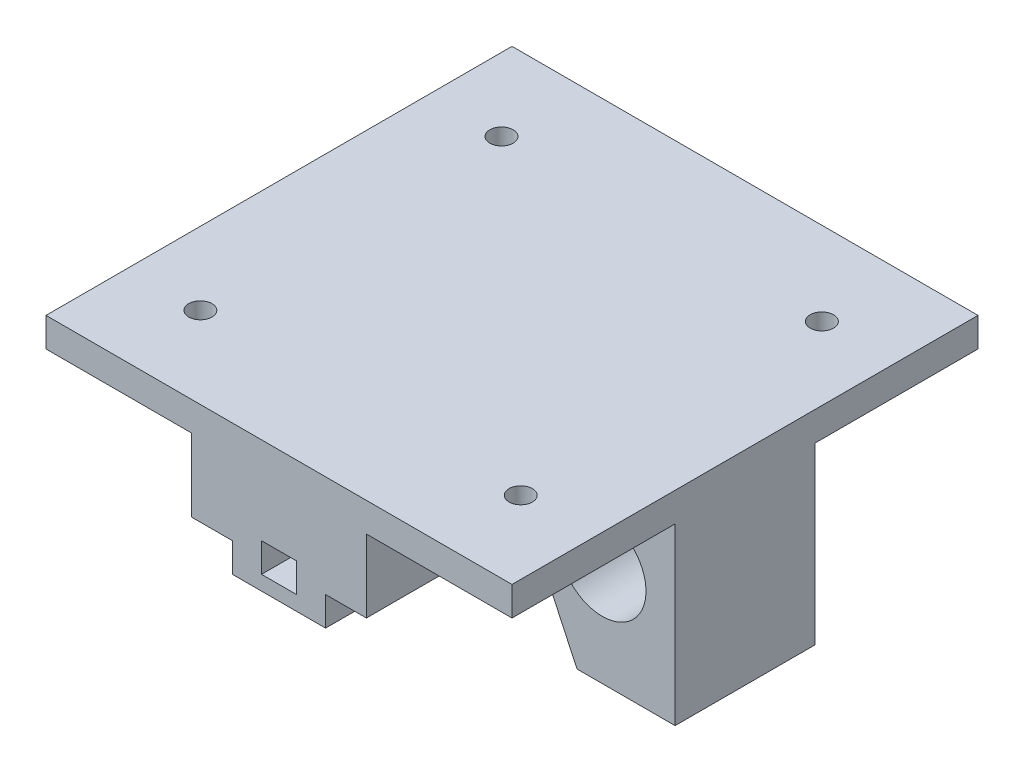
SolidWorks part; units mm, degrees
ref_plane "Front Plane" through (0, 0, 0) normal (0, 0, 1) x (1, 0, 0)
ref_plane "Top Plane" through (0, 0, 0) normal (0, 1, 0) x (1, 0, 0)
ref_plane "Right Plane" through (0, 0, 0) normal (1, 0, 0) x (0, 0, -1)
sketch "Sketch2" plane through (0, 0, 0) normal (0, 0, 1) x (1, 0, 0)
  line L14 (8, 0) -> (15, 0)
  line L16 (0, 17.5) -> (40, 17.5)
  line L17 (0, 17.5) -> (-40, 17.5)
  line L18 (23.1604, -17.5) -> (40, -17.5)
  line L19 (-23.1604, -17.5) -> (-40, -17.5)
  line L20 (-40, -17.5) -> (-40, 17.5)
  line L21 (40, 17.5) -> (40, -17.5)
  line L23 (-8, 0) -> (-15, 0)
  line L24 (-8, 0) -> (-8, -5)
  line L25 (8, 0) -> (8, -5)
  line L26 (-15, 0) -> (-23.1604, -17.5)
  line L27 (15, 0) -> (23.1604, -17.5)
  line L28 (-8, -5) -> (8, -5)
  line L29 (-3, 0) -> (-3, -2.5)
  line L30 (-3, 0) -> (-3, 2.5)
  line L31 (-3, 2.5) -> (3, 2.5)
  line L32 (3, 2.5) -> (3, 0)
  line L33 (3, 0) -> (3, -2.5)
  line L34 (3, -2.5) -> (-3, -2.5)
  circle A4 centre (-27.5, 0) radius 7.5
  circle A5 centre (27.5, 0) radius 7.5
  point P0 (0, 0)
  dimension "D1" = 40
  dimension "D7" = 5
  dimension "D2" = 35
  dimension "D4" = 40
  dimension "D9" = 5
  dimension "D10" = 2.5
  dimension "D11" = 2.5
  dimension "D12" = 115
  dimension "D13" = 115
extrude "Boss-Extrude2" add sketch "Sketch2" against normal blind 80
ref_plane "Plane2" through (0, -5, 0) normal (0, -1, 0) x (-1, 0, 0)
sketch "Sketch5" plane through (0, -5, 0) normal (0, -1, 0) x (-1, 0, 0)
  line L1 (-8, 80) -> (-8, 0) construction
  line L2 (-8, 70) -> (8, 70)
  line L3 (8, 80) -> (8, 0) construction
  line L5 (-8, 10) -> (8, 10)
  line L6 (8, 10) -> (8, 70)
  line L7 (-8, 70) -> (-8, 10)
ref_plane "Plane3" through (0, 17.5, 0) normal (0, 1, 0) x (1, 0, 0)
extrude "Cut-Extrude5" cut sketch "Sketch5" against normal blind 5
ref_plane "Plane4" through (0, 0, 0) normal (0, 0, 1) x (1, 0, 0)
sketch "Sketch6" plane through (0, 0, 0) normal (0, 0, 1) x (1, 0, 0)
  line L6 (-40, 12.5) -> (-40, -17.5)
  line L7 (-40, -17.5) -> (-23.1604, -17.5)
  line L8 (-23.1604, -17.5) -> (-15, 0)
  line L9 (-15, 0) -> (-15, 12.5)
  line L10 (-15, 12.5) -> (-40, 12.5)
  line L11 (40, 12.5) -> (40, -17.5)
  line L12 (40, -17.5) -> (23.1604, -17.5)
  line L13 (23.1604, -17.5) -> (40, -17.5) construction
  line L14 (23.1604, -17.5) -> (15, 0)
  line L15 (15, 0) -> (15, 12.5)
  line L16 (15, 12.5) -> (40, 12.5)
extrude "Cut-Extrude6" cut sketch "Sketch6" against normal blind 28
ref_plane "Plane5" through (0, 0, -80) normal (0, 0, -1) x (-1, 0, 0)
sketch "Sketch7" plane through (0, 0, -80) normal (0, 0, -1) x (-1, 0, 0)
  line L0 (-40, 12.5) -> (-40, -17.5)
  line L1 (-40, -17.5) -> (-23.1604, -17.5)
  line L2 (-23.1604, -17.5) -> (-15, 0)
  line L3 (-15, 0) -> (-23.1604, -17.5) construction
  line L4 (-15, 0) -> (-15, 12.5)
  line L5 (-15, 12.5) -> (-40, 12.5)
  line L6 (40, 12.5) -> (40, -17.5)
  line L7 (40, -17.5) -> (23.1604, -17.5)
  line L8 (23.1604, -17.5) -> (15, 0)
  line L9 (15, 0) -> (15, 12.5)
  line L10 (15, 12.5) -> (40, 12.5)
extrude "Cut-Extrude7" cut sketch "Sketch7" against normal blind 28
sketch "Sketch8" plane through (0, 17.5, 0) normal (0, 1, 0) x (1, 0, 0)
  circle A0 centre (27.5, 14) radius 2
  circle A3 centre (-27.5, 14) radius 2
  circle A5 centre (-27.5, 65.6972) radius 2
  circle A6 centre (27.5, 65.6972) radius 2
extrude "Cut-Extrude8" cut sketch "Sketch8" against normal blind 5
